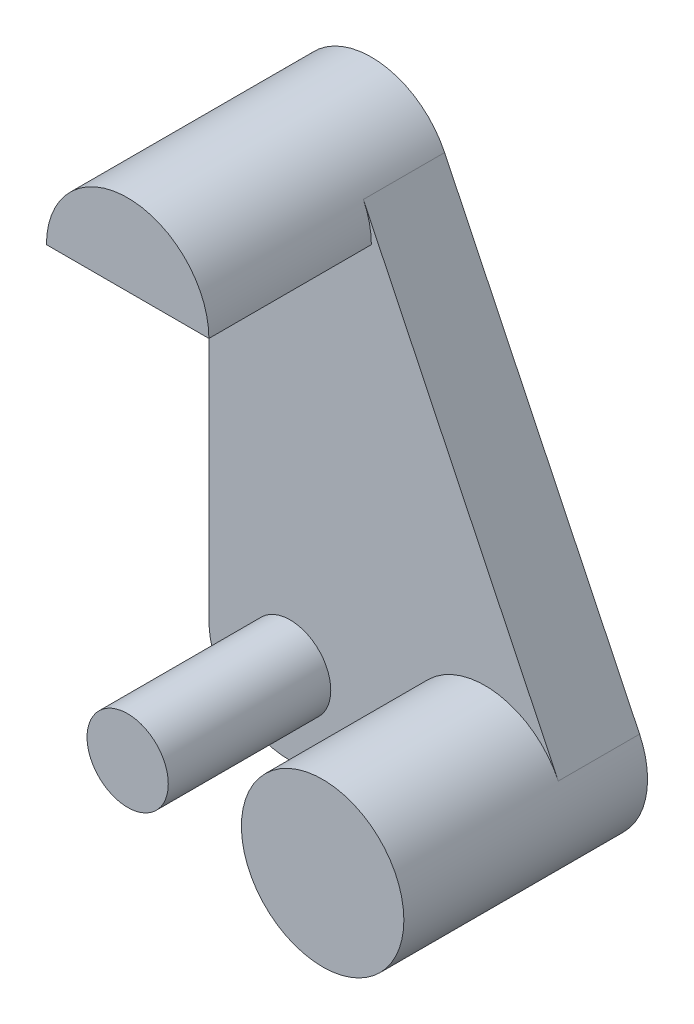
SolidWorks part; units mm, degrees
ref_plane "Plan de face" through (0, 0, 0) normal (0, 0, 1) x (1, 0, 0)
ref_plane "Plan de dessus" through (0, 0, 0) normal (0, 1, 0) x (1, 0, 0)
ref_plane "Plan de droite" through (0, 0, 0) normal (1, 0, 0) x (0, 0, -1)
sketch "Croquis1" plane through (0, 0, 0) normal (0, 0, 1) x (1, 0, 0)
  line L0 (-4.9922, 25.2791) -> (-4.9922, 0.2791)
  line L3 (0, -5) -> (12, -5)
  line L5 (4.5076, 27.1637) -> (16.5076, 2.1637)
  arc A4 (0, -5) -> (-4.9922, 0.2791) centre (0, 0) cw
  arc A6 (4.5076, 27.1637) -> (-4.9922, 24.7209) centre (0, 25) ccw
  arc A7 (12, -5) -> (16.5076, 2.1637) centre (12, 0) ccw
  dimension "D1" = 10
  dimension "D2" = 5
  dimension "D4" = 10
  dimension "D3" = 12
  dimension "D6" = 25
  dimension "D7" = 25
  dimension "D8" = 12
extrude "Saliente-Extruir1" add sketch "Croquis1" along normal blind 5 contours L3 A7 L5 A6 L0 A4
sketch "Croquis2" plane through (0, 0, 5) normal (0, 0, 1) x (1, 0, 0)
  line L0 (-5, 25) -> (5, 25)
  circle A0 centre (0, 0) radius 2.5
  circle A1 centre (12, 0) radius 5
  arc A2 (5, 25) -> (-5, 25) centre (0, 25) ccw
  dimension "D1" = 5
extrude "Saliente-Extruir2" add sketch "Croquis2" along normal blind 10
